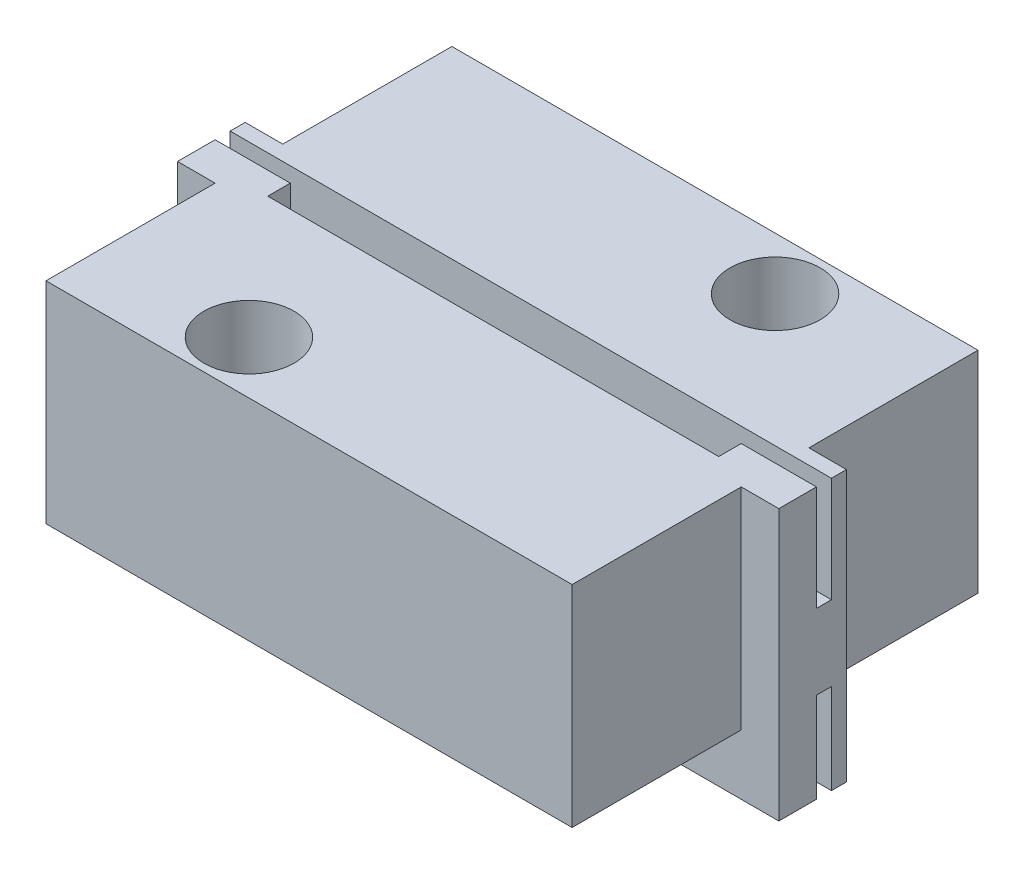
SolidWorks part; units mm, degrees
material "ABS"
ref_plane "Front Plane" through (0, 0, 0) normal (0, 0, 1) x (1, 0, 0)
ref_plane "Top Plane" through (0, 0, 0) normal (0, 1, 0) x (1, 0, 0)
ref_plane "Right Plane" through (0, 0, 0) normal (1, 0, 0) x (0, 0, -1)
sketch "Sketch1" plane through (0, 0, 0) normal (0, 1, 0) x (1, 0, 0)
  line L5 (-17.5, 13.5) -> (17.5, 13.5)
  line L6 (-17.5, 13.5) -> (-17.5, -13.5)
  line L7 (-17.5, -13.5) -> (17.5, -13.5)
  line L8 (17.5, 13.5) -> (17.5, -13.5)
  line L9 (-17.5, 13.5) -> (17.5, -13.5) construction
  line L10 (-17.5, -13.5) -> (17.5, 13.5) construction
  point P0 (0, 0)
  dimension "D1" = 35
  dimension "D2" = 27
extrude "Boss-Extrude1" add sketch "Sketch1" along normal blind 14
sketch "Sketch2" plane through (0, 14, 0) normal (0, 1, 0) x (1, 0, 0)
  line L2 (17.5, -13.5) -> (17.5, 13.5) construction
  line L3 (0, 13.5) -> (0, -13.5) construction
  line L4 (17.5, 13.5) -> (-17.5, 13.5) construction
  line L5 (-17.5, -13.5) -> (17.5, -13.5) construction
  circle A1 centre (7.5, 10) radius 1.75
  circle A4 centre (-7.5, -10) radius 1.75
  point P16 (0, 0)
  dimension "D1" = 15
  dimension "D3" = 3.5
  dimension "D5" = 3.5
  dimension "D6" = 3.5
  dimension "D2" = 20
  dimension "D4" = 10
extrude "Cut-Extrude1" cut sketch "Sketch2" against normal blind 14
sketch "Sketch9" plane through (0, 14, 0) normal (0, 1, 0) x (1, 0, 0)
  circle A3 centre (7.5, 10) radius 3
  circle A4 centre (-7.5, -10) radius 3
  dimension "D1" = 6
  dimension "D3" = 6
extrude "Cut-Extrude7" cut sketch "Sketch9" against normal blind 10
sketch "Sketch10" plane through (0, 0, 0) normal (0, -1, 0) x (1, 0, 0)
  line L0 (-17.5, -13.5) -> (-17.5, 13.5) construction
  line L1 (17.5, -2.25) -> (-17.5, -2.25)
  line L2 (17.5, -2.25) -> (17.5, 2.25)
  line L3 (17.5, 2.25) -> (-17.5, 2.25)
  line L4 (-17.5, -2.25) -> (-17.5, 2.25)
  line L5 (17.5, -2.25) -> (-17.5, 2.25) construction
  line L6 (17.5, 2.25) -> (-17.5, -2.25) construction
  point P0 (0, 0)
  dimension "D1" = 4.5
extrude "Boss-Extrude2" add sketch "Sketch10" along normal blind 4
sketch "Sketch11" plane through (0, -4, 0) normal (0, -1, 0) x (1, 0, 0)
  line L0 (-17.5, 2.25) -> (-17.5, -2.25) construction
  line L1 (17.5, -1.25) -> (-17.5, -1.25)
  line L2 (17.5, -1.25) -> (17.5, 1.25)
  line L3 (17.5, 1.25) -> (-17.5, 1.25)
  line L4 (-17.5, -1.25) -> (-17.5, 1.25)
  line L5 (17.5, -1.25) -> (-17.5, 1.25) construction
  line L6 (17.5, 1.25) -> (-17.5, -1.25) construction
  point P0 (0, 0)
  dimension "D1" = 2.5
extrude "Cut-Extrude8" cut sketch "Sketch11" against normal blind 6
sketch "Sketch12" plane through (-17.5, 0, 0) normal (-1, 0, 0) x (0, 0, 1)
  line L0 (-2.25, -4) -> (-2.25, 0) construction
  line L1 (-1.25, -4) -> (-2.25, -4) construction
  line L2 (2.25, -4) -> (1.25, -4) construction
  line L3 (2.25, -4) -> (2.25, 0) construction
  line L4 (1.25, 2) -> (1.25, -4) construction
  line L5 (1.25, 2) -> (-1.25, 2) construction
  line L6 (-1.25, 2) -> (-1.25, -4) construction
  line L7 (-2.25, -4) -> (-2.25, 0)
  line L8 (-1.25, -4) -> (-2.25, -4)
  line L9 (2.25, -4) -> (1.25, -4)
  line L10 (2.25, -4) -> (2.25, 0)
  line L11 (1.25, 2) -> (1.25, -4)
  line L12 (1.25, 2) -> (-1.25, 2)
  line L13 (-1.25, 2) -> (-1.25, -4)
  line L14 (-2.25, 0) -> (-2.25, 14)
  line L15 (-13.5, 14) -> (13.5, 14) construction
  line L16 (2.25, 0) -> (2.25, 14)
  line L17 (2.25, 14) -> (-2.25, 14)
extrude "Boss-Extrude3" add sketch "Sketch12" along normal blind 2.5
sketch "Sketch13" plane through (17.5, 0, 0) normal (1, 0, 0) x (0, 0, -1)
  line L0 (2.25, -4) -> (2.25, 0) construction
  line L1 (2.25, -4) -> (1.25, -4) construction
  line L2 (1.25, 2) -> (1.25, -4) construction
  line L3 (1.25, 2) -> (-1.25, 2) construction
  line L4 (-1.25, 2) -> (-1.25, -4) construction
  line L5 (-1.25, -4) -> (-2.25, -4) construction
  line L6 (-2.25, -4) -> (-2.25, 0) construction
  line L7 (2.25, -4) -> (2.25, 0)
  line L8 (2.25, -4) -> (1.25, -4)
  line L9 (1.25, 2) -> (1.25, -4)
  line L10 (1.25, 2) -> (-1.25, 2)
  line L11 (-1.25, 2) -> (-1.25, -4)
  line L12 (-1.25, -4) -> (-2.25, -4)
  line L13 (-2.25, -4) -> (-2.25, 0)
  line L14 (-2.25, 0) -> (-2.25, 14)
  line L15 (-13.5, 14) -> (13.5, 14) construction
  line L16 (-2.25, 14) -> (2.25, 14)
  line L17 (2.25, 14) -> (2.25, 0)
extrude "Boss-Extrude4" add sketch "Sketch13" along normal blind 2.5
sketch "Sketch14" plane through (0, 0, 1.25) normal (0, 0, -1) x (-1, 0, 0)
  line L0 (-20, -4) -> (20, -4) construction
  line L1 (-20, 2) -> (-15, 2)
  line L2 (-20, 2) -> (-20, -4)
  line L3 (-20, -4) -> (-15, -4)
  line L4 (-15, 2) -> (-15, -4)
  line L6 (20, 2) -> (15, 2)
  line L7 (20, 2) -> (20, -4)
  line L8 (20, -4) -> (15, -4)
  line L9 (15, 2) -> (15, -4)
  dimension "D1" = 5
  dimension "D2" = 5
extrude "Boss-Extrude5" add sketch "Sketch14" along normal blind 1.5
sketch "Sketch15" plane through (0, 14, 0) normal (0, 1, 0) x (1, 0, 0)
  line L0 (-20, -2.25) -> (-20, 2.25) construction
  line L1 (20, -1.25) -> (-20, -1.25)
  line L2 (20, -1.25) -> (20, 1.25)
  line L3 (20, 1.25) -> (-20, 1.25)
  line L4 (-20, -1.25) -> (-20, 1.25)
  line L5 (20, -1.25) -> (-20, 1.25) construction
  line L6 (20, 1.25) -> (-20, -1.25) construction
  point P0 (0, 0)
  dimension "D1" = 2.5
extrude "Cut-Extrude9" cut sketch "Sketch15" against normal blind 7
sketch "Sketch16" plane through (0, 0, 1.25) normal (0, 0, -1) x (-1, 0, 0)
  line L0 (20, 14) -> (-20, 14) construction
  line L1 (-20, 7) -> (-15, 7)
  line L2 (-20, 7) -> (-20, 14)
  line L3 (-20, 14) -> (-15, 14)
  line L4 (-15, 7) -> (-15, 14)
  line L6 (20, 7) -> (15, 7)
  line L7 (20, 7) -> (20, 14)
  line L8 (20, 14) -> (15, 14)
  line L9 (15, 7) -> (15, 14)
  dimension "D1" = 5
  dimension "D2" = 5
extrude "Boss-Extrude6" add sketch "Sketch16" along normal blind 1.5
